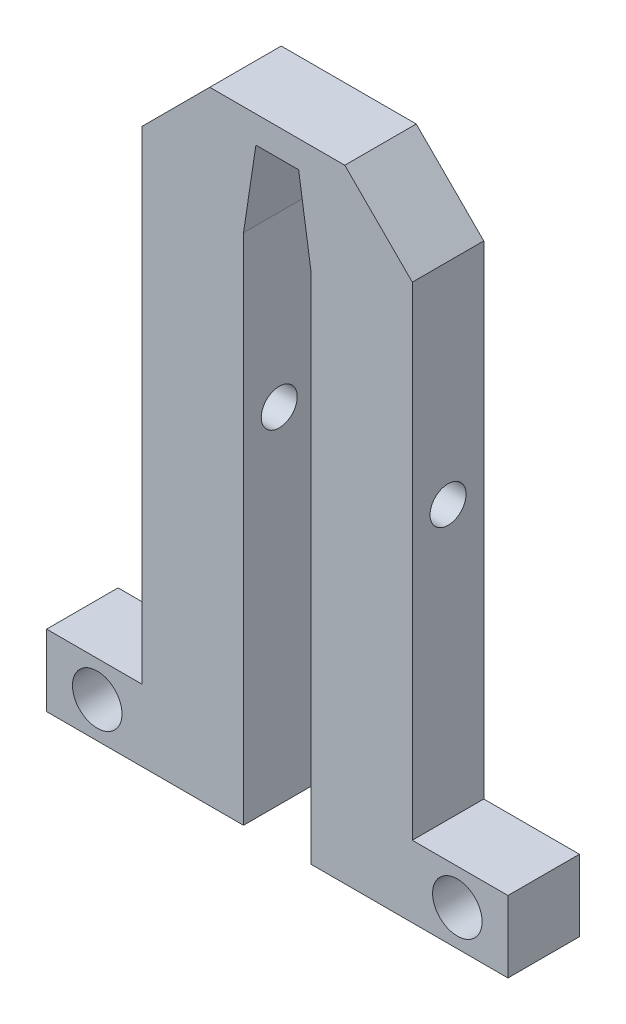
SolidWorks part; units mm, degrees
ref_plane "Front Plane" through (0, 0, 0) normal (0, 0, 1) x (1, 0, 0)
ref_plane "Top Plane" through (0, 0, 0) normal (0, 1, 0) x (1, 0, 0)
ref_plane "Right Plane" through (0, 0, 0) normal (1, 0, 0) x (0, 0, -1)
sketch "Sketch1" plane through (0, 0, 0) normal (0, 0, 1) x (1, 0, 0)
  line L0 (-10.25, 0) -> (10.25, 0) construction
  line L1 (0, 0) -> (0, 27.65) construction
  line L2 (6, 27.65) -> (-6, 27.65)
  line L3 (-6, 27.65) -> (-6, 3.175)
  line L4 (-10.25, 3.175) -> (-10.25, 0)
  line L5 (-10.25, 0) -> (-1.5, 0)
  line L6 (-0.95, 26.45) -> (-1.5, 22.8)
  line L7 (-0.95, 26.45) -> (0.95, 26.45)
  line L8 (-1.5, 22.8) -> (-1.5, 0)
  line L9 (-6, 3.175) -> (-10.25, 3.175)
  line L10 (10.25, 0) -> (1.5, 0)
  line L11 (10.25, 3.175) -> (10.25, 0)
  line L12 (6, 3.175) -> (10.25, 3.175)
  line L13 (1.5, 22.8) -> (1.5, 0)
  line L14 (6, 27.65) -> (6, 3.175)
  line L15 (0.95, 26.45) -> (1.5, 22.8)
  point P4 (0, 0)
  point P9 (0, 27.65)
  point P20 (0, 26.45)
  dimension "D1" = 20.5
  dimension "D2" = 27.65
  dimension "D3" = 6
  dimension "D4" = 0.95
  dimension "D5" = 26.45
  dimension "D6" = 1.5
  dimension "D7" = 22.8
  dimension "D8" = 3.175
extrude "Boss-Extrude1" add sketch "Sketch1" along normal blind 3.175
chamfer "Chamfer1" distance 3 angle 45 2 edges at (-6, 27.65, 1.5875) (6, 27.65, 1.5875)
hole_wizard "Tap Drill for M2x0.4 Tap1" positions "Sketch2" profile "Sketch3" hole size "M2x0.4" standard "ANSI Metric" end condition through all
sketch "Sketch2" plane through (6, 0, 0) normal (1, 0, 0) x (0, 0, -1)
  line L0 (-1.5875, 15.3) -> (-1.5875, 0) construction
  line L1 (-3.175, 0) -> (0, 0) construction
  point P0 (-1.5875, 15.3)
  dimension "D1" = 15.3
sketch "Sketch3" plane through (6, 15.3, 1.5875) normal (0, 1, 0) x (0, 0, -1)
  line L0 (0, 0) -> (0, 16.25)
  line L1 (0, 16.25) -> (0.8, 16.25)
  line L2 (0.8, 16.25) -> (0.8, 0)
  line L5 (0.8, 0) -> (0, 0)
  line L11 (0, -6.35) -> (0, 107.95) construction
  dimension "Thru Hole Dia." = 1.6
  dimension "Thru Hole Depth" = 16.25
hole_wizard "M2 Clearance Hole1" positions "Sketch4" profile "Sketch5" hole size "M2" standard "ANSI Metric" end condition through all
sketch "Sketch4" plane through (0, 0, 3.175) normal (0, 0, 1) x (1, 0, 0)
  line L0 (-8, 1.5875) -> (8, 1.5875) construction
  line L2 (0, 0) -> (0, 1.5875) construction
  line L4 (-8, 1.5875) -> (-10.25, 1.5875) construction
  line L5 (-10.25, 3.175) -> (-10.25, 0) construction
  point P0 (-8, 1.5875)
  point P2 (8, 1.5875)
  dimension "D1" = 16
sketch "Sketch5" plane through (-8, 1.5875, 3.175) normal (1, 0, 0) x (0, -1, 0)
  line L0 (0, 0) -> (0, 3.175)
  line L1 (0, 3.175) -> (1.1, 3.175)
  line L2 (1.1, 3.175) -> (1.1, 0)
  line L5 (1.1, 0) -> (0, 0)
  line L11 (0, -6.35) -> (0, 107.95) construction
  dimension "Thru Hole Dia." = 2.2
  dimension "Thru Hole Depth" = 3.175
